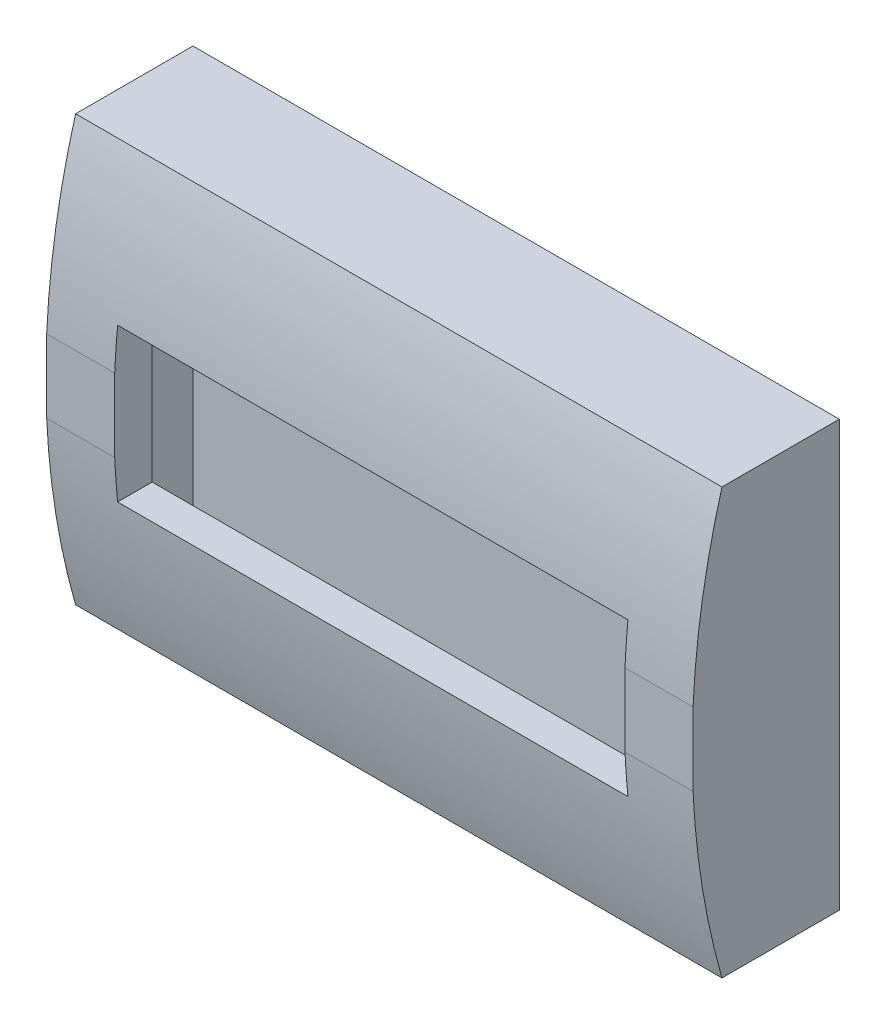
SolidWorks part; units mm, degrees
ref_plane "Alzado" through (0, 0, 0) normal (0, 0, 1) x (1, 0, 0)
ref_plane "Planta" through (0, 0, 0) normal (0, 1, 0) x (1, 0, 0)
ref_plane "Vista lateral" through (0, 0, 0) normal (1, 0, 0) x (0, 0, -1)
sketch "Croquis1" plane through (0, 0, 0) normal (0, 0, 1) x (1, 0, 0)
  line L1 (-190, -125) -> (190, -125)
  line L2 (-190, -125) -> (-190, 125)
  line L3 (-190, 125) -> (190, 125)
  line L4 (190, -125) -> (190, 125)
  line L5 (-190, -125) -> (190, 125) construction
  line L6 (-190, 125) -> (190, -125) construction
  point P0 (0, 0)
  dimension "D1" = 380
  dimension "D2" = 250
extrude "Saliente-Extruir1" add sketch "Croquis1" along normal blind 64
sketch "Croquis2" plane through (0, 0, 64) normal (0, 0, 1) x (1, 0, 0)
  line L0 (0, 125) -> (0, -125) construction
  line L1 (190, 125) -> (-190, 125) construction
  line L2 (-190, -125) -> (190, -125) construction
  line L3 (190, -125) -> (190, 125) construction
  line L4 (-186, -121) -> (186, -121)
  line L5 (-186, -121) -> (-186, 121)
  line L6 (-186, 121) -> (186, 121)
  line L7 (186, -121) -> (186, 121)
  line L8 (-186, -121) -> (186, 121) construction
  line L9 (-186, 121) -> (186, -121) construction
  point P6 (0, 0)
  dimension "D1" = 4
  dimension "D2" = 4
extrude "Cortar-Extruir1" cut sketch "Croquis2" against normal blind 60
sketch "Croquis3" plane through (0, 0, 64) normal (0, 0, 1) x (1, 0, 0)
  line L1 (-190, 125) -> (190, 125)
  line L2 (-190, 125) -> (-190, -125)
  line L3 (-190, -125) -> (190, -125)
  line L4 (190, 125) -> (190, -125)
extrude "Saliente-Extruir2" add sketch "Croquis3" along normal blind 22
sketch "Croquis5" plane through (0, 0, 86) normal (0, 0, 1) x (1, 0, 0)
  line L0 (0, 125) -> (0, -125) construction
  line L1 (190, 125) -> (-190, 125) construction
  line L2 (-190, -125) -> (190, -125) construction
  line L4 (-150, -45) -> (150, -45)
  line L5 (-150, -45) -> (-150, 45)
  line L6 (-150, 45) -> (150, 45)
  line L7 (150, -45) -> (150, 45)
  line L8 (-150, -45) -> (150, 45) construction
  line L9 (-150, 45) -> (150, -45) construction
  point P6 (0, 0)
  dimension "D1" = 90
  dimension "D2" = 300
extrude "Cortar-Extruir3" cut sketch "Croquis5" against normal blind 41
sketch "Croquis4" plane through (-190, 0, 0) normal (-1, 0, 0) x (0, 0, 1)
  line L0 (69, 125) -> (69, 152.4787)
  line L1 (69, 152.4787) -> (170.6718, 152.4787)
  line L2 (170.6718, 152.4787) -> (170.6718, -144.8862)
  line L3 (170.6718, -144.8862) -> (69, -144.8862)
  line L4 (86, 125) -> (0, 125) construction
  line L5 (69, -144.8862) -> (69, -125)
  line L6 (86, 125) -> (86, -125) construction
  line L9 (86, -125) -> (0, -125) construction
  arc A0 (69, -125) -> (69, 125) centre (-368.4661, 0) ccw
  dimension "D1" = 17
  dimension "D2" = 17
extrude "Cortar-Extruir2" cut sketch "Croquis4" against normal up to surface (380 mm away) up to face at (190, 0, 43)
